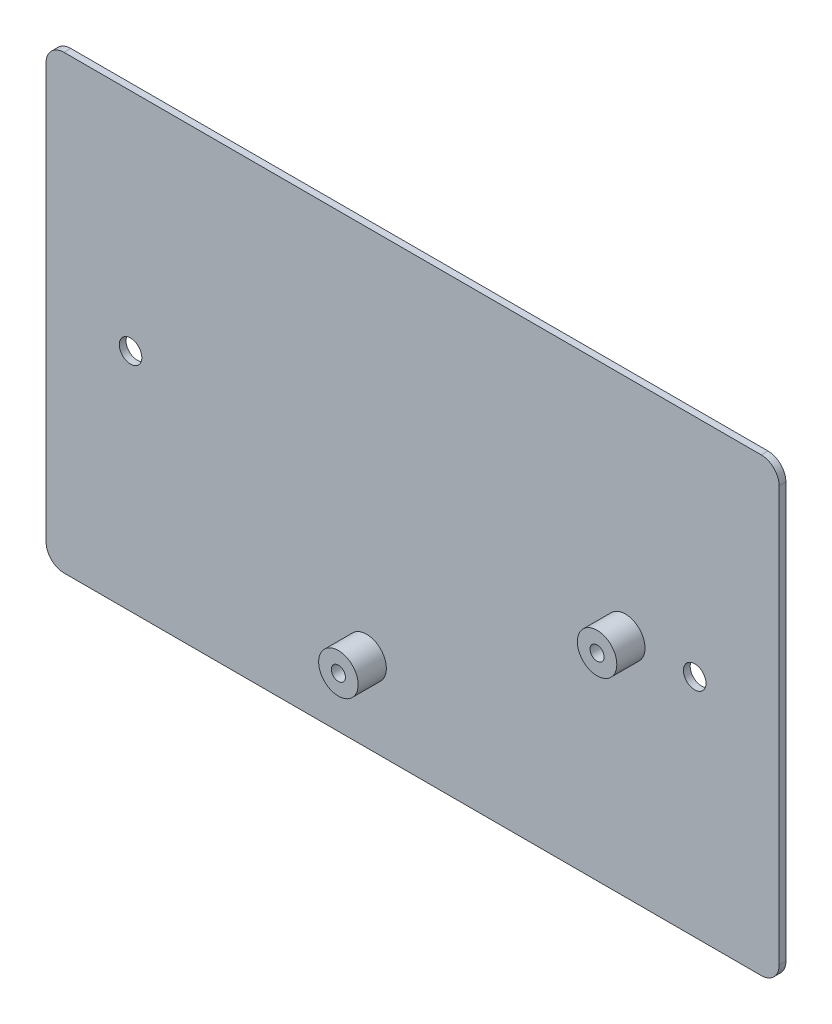
SolidWorks part; units mm, degrees
ref_plane "Front Plane" through (0, 0, 0) normal (0, 0, 1) x (1, 0, 0)
ref_plane "Top Plane" through (0, 0, 0) normal (0, 1, 0) x (1, 0, 0)
ref_plane "Right Plane" through (0, 0, 0) normal (1, 0, 0) x (0, 0, -1)
sketch "Sketch1" plane through (0, 0, 0) normal (0, 0, 1) x (1, 0, 0)
  line L1 (-64.965, -39.965) -> (64.965, -39.965)
  line L2 (-64.965, -39.965) -> (-64.965, 39.965)
  line L3 (-64.965, 39.965) -> (64.965, 39.965)
  line L4 (64.965, -39.965) -> (64.965, 39.965)
  line L5 (-64.965, -39.965) -> (64.965, 39.965) construction
  line L6 (-64.965, 39.965) -> (64.965, -39.965) construction
  point P0 (0, 0)
  dimension "D1" = 79.93
  dimension "D2" = 129.93
extrude "Boss-Extrude1" add sketch "Sketch1" along normal blind 1.2
fillet "Fillet1" radius 3.175 4 edges at (-64.965, 39.965, 0.6) (-64.965, -39.965, 0.6) (64.965, -39.965, 0.6) (64.965, 39.965, 0.6)
sketch "Sketch3" plane through (0, 0, 1.2) normal (0, 0, 1) x (1, 0, 0)
  line L0 (-64.965, 0) -> (64.965, 0) construction
  line L1 (-64.965, 36.79) -> (-64.965, -36.79) construction
  line L2 (64.965, -36.79) -> (64.965, 36.79) construction
  line L3 (0, 39.965) -> (0, -39.965) construction
  line L4 (61.79, 39.965) -> (-61.79, 39.965) construction
  line L5 (-61.79, -39.965) -> (61.79, -39.965) construction
  circle A0 centre (-50, 0) radius 2
  circle A1 centre (50, 0) radius 2
  dimension "D1" = 4
  dimension "D2" = 50
extrude "Cut-Extrude2" cut sketch "Sketch3" against normal up to next
sketch "Sketch2" plane through (0, 0, 1.2) normal (0, 0, 1) x (1, 0, 0)
  line L0 (-64.965, 0) -> (64.965, 0) construction
  line L1 (-64.965, 36.79) -> (-64.965, -36.79) construction
  line L2 (64.965, -36.79) -> (64.965, 36.79) construction
  line L4 (61.79, 39.965) -> (-61.79, 39.965) construction
  line L5 (-61.79, -39.965) -> (61.79, -39.965) construction
  line L6 (-8.1569, 39.965) -> (-8.1569, -39.965) construction
  circle A0 centre (-8.1569, -26.04) radius 1.25
  circle A1 centre (37.6931, 0) radius 1.25
  point P18 (0, -13.02)
  point P19 (-27.9881, 40.755)
  dimension "D1" = 2.5
  dimension "D2" = 2.5
  dimension "D5" = 26.04
  dimension "D6" = 45.85
extrude "Cut-Extrude1" cut sketch "Sketch2" against normal up to next and the other way through all
sketch "Sketch4" plane through (0, 0, 1.2) normal (0, 0, 1) x (1, 0, 0)
  circle A0 centre (-8.1569, -26.04) radius 3.5
  circle A1 centre (37.6931, 0) radius 3.5
  circle A9 centre (-8.1569, -26.04) radius 1.25
  circle A10 centre (37.6931, 0) radius 1.25
  dimension "D1" = 7
  dimension "D2" = 7
  dimension "D3" = 2.5
  dimension "D4" = 2.5
extrude "Boss-Extrude2" add sketch "Sketch4" along normal blind 5
equation "\"Box_Width\" = 79.93mm"
equation "\"Box_Length\" = 129.93mm"
equation "\"LoggerMount_Width\" = 26.04mm"
equation "\"LoggerMount_Length\" = 45.85mm"
equation "\"LoggerMount_Hole\"= 2.5mm"
equation "\"Box_Hole\"= 4mm"
equation "\"D1@Sketch1\"=\"Box_Width\""
equation "\"D2@Sketch1\"=\"Box_Length\""
equation "\"D1@Sketch2\"=\"LoggerMount_Hole\""
equation "\"D2@Sketch2\"=\"LoggerMount_Hole\""
equation "\"D5@Sketch2\"= \"LoggerMount_Width\""
equation "\"D1@Sketch3\"=\"Box_Hole\""
equation "\"Box_HoleSpacing\"= 100mm"
equation "\"D2@Sketch3\"= \"Box_HoleSpacing\"/2"
equation "\"D3@Sketch4\"=\"LoggerMount_Hole\""
equation "\"D4@Sketch4\"=\"LoggerMount_Hole\""
equation "\"D6@Sketch2\"=\"LoggerMount_Length\""
